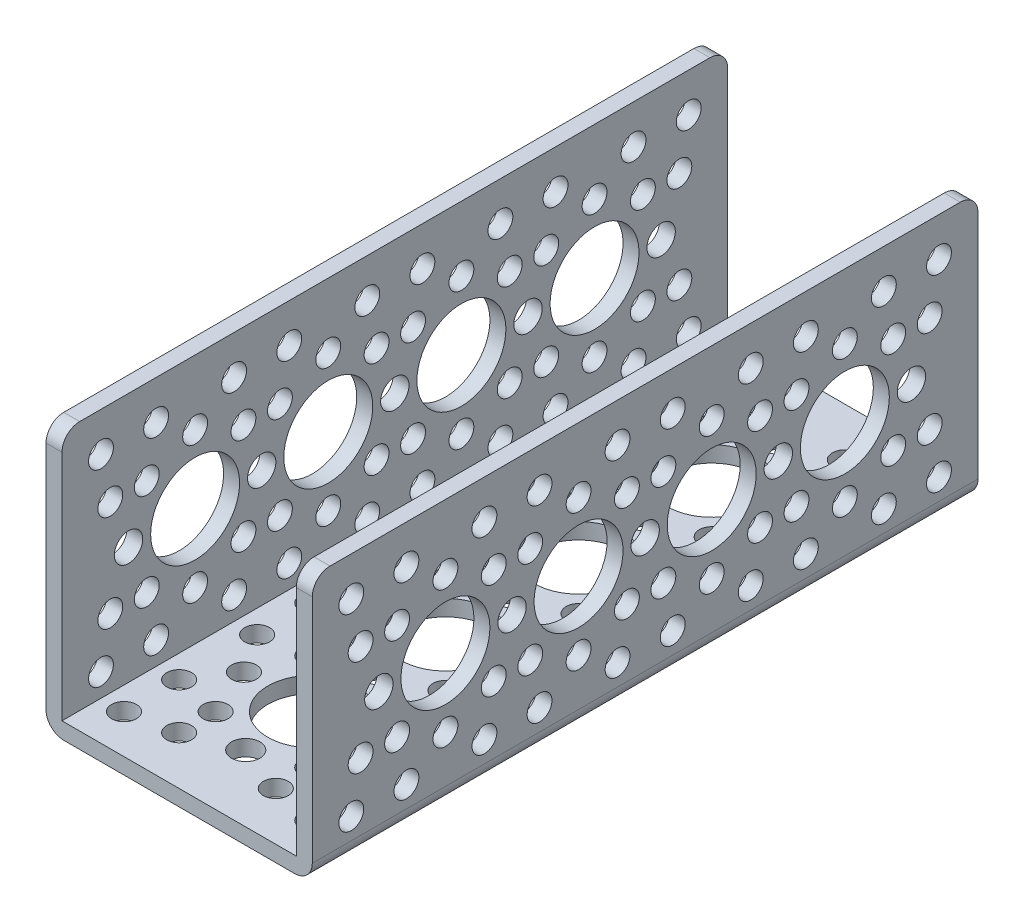
SolidWorks part; units mm, degrees
ref_plane "Front Plane" through (0, 0, 0) normal (0, 0, 1) x (1, 0, 0)
ref_plane "Top Plane" through (0, 0, 0) normal (0, 1, 0) x (1, 0, 0)
ref_plane "Right Plane" through (0, 0, 0) normal (1, 0, 0) x (0, 0, -1)
ref_plane "Plane1" through (0, 0, 0) normal (0, -1, 0) x (1, 0, 0)
sketch "Sketch1" plane through (0, 0, 0) normal (0, -1, 0) x (1, 0, 0)
  line L0 (38.1, 95.25) -> (0, 95.25)
  line L1 (0, 95.25) -> (0, 0)
  line L2 (0, 0) -> (38.1, 0)
  line L3 (38.1, 0) -> (38.1, 95.25)
extrude "Boss-Extrude1" add sketch "Sketch1" against normal blind 38.1
sketch "Sketch2" plane through (0, 0, 95.25) normal (0, 0, 1) x (1, 0, 0)
  line L0 (35.814, 38.1) -> (2.286, 38.1)
  line L1 (2.286, 38.1) -> (2.286, 2.286)
  line L2 (2.286, 2.286) -> (35.814, 2.286)
  line L3 (35.814, 2.286) -> (35.814, 38.1)
extrude "Cut-Extrude1" cut sketch "Sketch2" against normal through all
hole_wizard "Hole1" positions "Sketch4" profile "Sketch3" legacy
sketch "Sketch4" plane through (38.1, 0, 0) normal (1, 0, 0) x (0, 0, -1)
  point P0 (-38.1, 19.05)
  point P1 (-19.05, 19.05)
  point P2 (-57.15, 19.05)
  point P3 (-76.2, 19.05)
sketch "Sketch3" plane through (38.1, 19.05, 38.1) normal (0, 1, 0) x (0, 0, -1)
  line L0 (0, 0) -> (0, 2.286)
  line L1 (0, 2.286) -> (6.3627, 2.286)
  line L2 (6.3627, 2.286) -> (6.3627, 0)
  line L3 (6.3627, 0) -> (0, 0)
  line L4 (0, 110) -> (0, -10) construction
  dimension "Diameter" = 12.7254
  dimension "Depth" = 2.286
hole_wizard "#5 Clearance Hole1" positions "Sketch6" profile "Sketch5" hole size "#5" standard "ANSI Inch"
sketch "Sketch6" plane through (38.1, 0, 0) normal (1, 0, 0) x (0, 0, -1)
  point P0 (-81.7796, 5.5796)
  point P1 (-88.3352, 12.1352)
  point P2 (-81.7796, 32.5204)
  point P3 (-88.3352, 25.9648)
  point P4 (-13.4704, 5.5796)
  point P5 (-6.9148, 12.1352)
  point P6 (-13.4704, 32.5204)
  point P7 (-6.9148, 25.9648)
  point P8 (-62.7296, 5.5796)
  point P9 (-43.6796, 5.5796)
  point P10 (-24.6296, 5.5796)
  point P11 (-62.7296, 32.5204)
  point P12 (-43.6796, 32.5204)
  point P13 (-24.6296, 32.5204)
  point P14 (-89.6704, 5.5796)
  point P15 (-89.6704, 32.5204)
  point P16 (-70.6204, 5.5796)
  point P17 (-70.6204, 32.5204)
  point P18 (-51.5704, 5.5796)
  point P19 (-51.5704, 32.5204)
  point P20 (-38.1, 9.271)
  point P21 (-45.0148, 12.1352)
  point P22 (-45.0148, 25.9648)
  point P23 (-38.1, 28.829)
  point P24 (-31.1852, 25.9648)
  point P25 (-31.1852, 12.1352)
  point P26 (-32.5204, 5.5796)
  point P27 (-32.5204, 32.5204)
  point P28 (-5.5796, 5.5796)
  point P29 (-5.5796, 32.5204)
  point P30 (-12.1352, 12.1352)
  point P31 (-19.05, 9.271)
  point P32 (-25.9648, 12.1352)
  point P33 (-25.9648, 25.9648)
  point P34 (-19.05, 28.829)
  point P35 (-12.1352, 25.9648)
  point P36 (-50.2352, 12.1352)
  point P37 (-69.2852, 12.1352)
  point P38 (-50.2352, 25.9648)
  point P39 (-69.2852, 25.9648)
  point P40 (-57.15, 28.829)
  point P41 (-76.2, 28.829)
  point P42 (-64.0648, 25.9648)
  point P43 (-83.1148, 25.9648)
  point P44 (-64.0648, 12.1352)
  point P45 (-83.1148, 12.1352)
  point P46 (-57.15, 9.271)
  point P47 (-76.2, 9.271)
sketch "Sketch5" plane through (38.1, 5.5796, 81.7796) normal (0, 1, 0) x (0, 0, -1)
  line L0 (0, 0) -> (0, 2.286)
  line L1 (0, 2.286) -> (1.778, 2.286)
  line L2 (1.778, 2.286) -> (1.778, 0)
  line L5 (1.778, 0) -> (0, 0)
  line L11 (0, -6.35) -> (0, 107.95) construction
  dimension "Thru Hole Dia." = 3.556
  dimension "Thru Hole Depth" = 2.286
hole_wizard "#6 Clearance Hole1" positions "Sketch8" profile "Sketch7" hole size "#6" standard "ANSI Inch"
sketch "Sketch8" plane through (38.1, 0, 0) normal (1, 0, 0) x (0, 0, -1)
  point P0 (-85.725, 19.05)
  point P1 (-66.675, 19.05)
  point P2 (-47.625, 19.05)
  point P3 (-28.575, 19.05)
  point P4 (-9.525, 19.05)
sketch "Sketch7" plane through (38.1, 19.05, 85.725) normal (0, 1, 0) x (0, 0, -1)
  line L0 (0, 0) -> (0, 2.286)
  line L1 (0, 2.286) -> (2.032, 2.286)
  line L2 (2.032, 2.286) -> (2.032, 0)
  line L5 (2.032, 0) -> (0, 0)
  line L11 (0, -6.35) -> (0, 107.95) construction
  dimension "Thru Hole Dia." = 4.064
  dimension "Thru Hole Depth" = 2.286
hole_wizard "Hole2" positions "Sketch10" profile "Sketch9" legacy
sketch "Sketch10" plane through (0, 0, 0) normal (0, -1, 0) x (-1, 0, 0)
  point P0 (-19.05, -76.2)
  point P1 (-19.05, -57.15)
  point P2 (-19.05, -38.1)
  point P3 (-19.05, -19.05)
sketch "Sketch9" plane through (19.05, 0, 76.2) normal (1, 0, 0) x (0, 0, -1)
  line L0 (0, 0) -> (0, 38.1)
  line L1 (0, 38.1) -> (6.3627, 38.1)
  line L2 (6.3627, 38.1) -> (6.3627, 0)
  line L3 (6.3627, 0) -> (0, 0)
  line L4 (0, 110) -> (0, -10) construction
  dimension "Diameter" = 12.7254
  dimension "Depth" = 38.1
hole_wizard "#6 Clearance Hole2" positions "Sketch12" profile "Sketch11" hole size "#6" standard "ANSI Inch"
sketch "Sketch12" plane through (0, 0, 0) normal (0, -1, 0) x (-1, 0, 0)
  point P0 (-19.05, -85.725)
  point P1 (-19.05, -66.675)
  point P2 (-19.05, -47.625)
  point P3 (-19.05, -28.575)
  point P4 (-19.05, -9.525)
sketch "Sketch11" plane through (19.05, 0, 85.725) normal (1, 0, 0) x (0, 0, -1)
  line L0 (0, 0) -> (0, 38.1)
  line L1 (0, 38.1) -> (2.032, 38.1)
  line L2 (2.032, 38.1) -> (2.032, 0)
  line L5 (2.032, 0) -> (0, 0)
  line L11 (0, -6.35) -> (0, 107.95) construction
  dimension "Thru Hole Dia." = 4.064
  dimension "Thru Hole Depth" = 38.1
hole_wizard "#5 Clearance Hole2" positions "Sketch14" profile "Sketch13" hole size "#5" standard "ANSI Inch"
sketch "Sketch14" plane through (0, 0, 0) normal (0, -1, 0) x (-1, 0, 0)
  point P0 (-5.5796, -89.6704)
  point P1 (-5.5796, -81.7796)
  point P2 (-12.1352, -88.3352)
  point P3 (-32.5204, -89.6704)
  point P4 (-32.5204, -81.7796)
  point P5 (-25.9648, -88.3352)
  point P6 (-5.5796, -70.6204)
  point P7 (-5.5796, -62.7296)
  point P8 (-32.5204, -70.6204)
  point P9 (-32.5204, -62.7296)
  point P10 (-5.5796, -51.5704)
  point P11 (-5.5796, -43.6796)
  point P12 (-32.5204, -51.5704)
  point P13 (-32.5204, -43.6796)
  point P14 (-12.1352, -69.2852)
  point P15 (-9.271, -76.2)
  point P16 (-12.1352, -83.1148)
  point P17 (-25.9648, -83.1148)
  point P18 (-28.829, -76.2)
  point P19 (-25.9648, -69.2852)
  point P20 (-12.1352, -50.2352)
  point P21 (-9.271, -57.15)
  point P22 (-12.1352, -64.0648)
  point P23 (-25.9648, -64.0648)
  point P24 (-28.829, -57.15)
  point P25 (-25.9648, -50.2352)
  point P26 (-9.271, -38.1)
  point P27 (-12.1352, -45.0148)
  point P28 (-25.9648, -45.0148)
  point P29 (-28.829, -38.1)
  point P30 (-5.5796, -32.5204)
  point P31 (-5.5796, -24.6296)
  point P32 (-12.1352, -31.1852)
  point P33 (-32.5204, -32.5204)
  point P34 (-32.5204, -24.6296)
  point P35 (-25.9648, -31.1852)
  point P36 (-5.5796, -5.5796)
  point P37 (-5.5796, -13.4704)
  point P38 (-12.1352, -6.9148)
  point P39 (-32.5204, -5.5796)
  point P40 (-32.5204, -13.4704)
  point P41 (-25.9648, -6.9148)
  point P42 (-12.1352, -12.1352)
  point P43 (-9.271, -19.05)
  point P44 (-12.1352, -25.9648)
  point P45 (-25.9648, -25.9648)
  point P46 (-28.829, -19.05)
  point P47 (-25.9648, -12.1352)
sketch "Sketch13" plane through (5.5796, 0, 89.6704) normal (1, 0, 0) x (0, 0, -1)
  line L0 (0, 0) -> (0, 38.1)
  line L1 (0, 38.1) -> (1.778, 38.1)
  line L2 (1.778, 38.1) -> (1.778, 0)
  line L5 (1.778, 0) -> (0, 0)
  line L11 (0, -6.35) -> (0, 107.95) construction
  dimension "Thru Hole Dia." = 3.556
  dimension "Thru Hole Depth" = 38.1
hole_wizard "Hole3" positions "Sketch16" profile "Sketch15" legacy
sketch "Sketch16" plane through (0, 0, 0) normal (-1, 0, 0) x (0, 0, 1)
  point P0 (38.1, 19.05)
  point P1 (19.05, 19.05)
  point P2 (57.15, 19.05)
  point P3 (76.2, 19.05)
sketch "Sketch15" plane through (0, 19.05, 38.1) normal (0, 1, 0) x (0, 0, 1)
  line L0 (0, 0) -> (0, 38.1)
  line L1 (0, 38.1) -> (6.3627, 38.1)
  line L2 (6.3627, 38.1) -> (6.3627, 0)
  line L3 (6.3627, 0) -> (0, 0)
  line L4 (0, 110) -> (0, -10) construction
  dimension "Diameter" = 12.7254
  dimension "Depth" = 38.1
hole_wizard "#5 Clearance Hole3" positions "Sketch18" profile "Sketch17" hole size "#5" standard "ANSI Inch"
sketch "Sketch18" plane through (0, 0, 0) normal (-1, 0, 0) x (0, 0, 1)
  point P0 (81.7796, 5.5796)
  point P1 (88.3352, 12.1352)
  point P2 (81.7796, 32.5204)
  point P3 (88.3352, 25.9648)
  point P4 (13.4704, 5.5796)
  point P5 (6.9148, 12.1352)
  point P6 (13.4704, 32.5204)
  point P7 (6.9148, 25.9648)
  point P8 (62.7296, 5.5796)
  point P9 (43.6796, 5.5796)
  point P10 (24.6296, 5.5796)
  point P11 (62.7296, 32.5204)
  point P12 (43.6796, 32.5204)
  point P13 (24.6296, 32.5204)
  point P14 (89.6704, 5.5796)
  point P15 (89.6704, 32.5204)
  point P16 (70.6204, 5.5796)
  point P17 (70.6204, 32.5204)
  point P18 (51.5704, 5.5796)
  point P19 (51.5704, 32.5204)
  point P20 (31.1852, 12.1352)
  point P21 (38.1, 9.271)
  point P22 (45.0148, 12.1352)
  point P23 (45.0148, 25.9648)
  point P24 (38.1, 28.829)
  point P25 (31.1852, 25.9648)
  point P26 (32.5204, 5.5796)
  point P27 (32.5204, 32.5204)
  point P28 (5.5796, 5.5796)
  point P29 (5.5796, 32.5204)
  point P30 (12.1352, 12.1352)
  point P31 (19.05, 9.271)
  point P32 (25.9648, 12.1352)
  point P33 (25.9648, 25.9648)
  point P34 (19.05, 28.829)
  point P35 (12.1352, 25.9648)
  point P36 (50.2352, 25.9648)
  point P37 (69.2852, 25.9648)
  point P38 (57.15, 28.829)
  point P39 (76.2, 28.829)
  point P40 (64.0648, 25.9648)
  point P41 (83.1148, 25.9648)
  point P42 (64.0648, 12.1352)
  point P43 (83.1148, 12.1352)
  point P44 (57.15, 9.271)
  point P45 (76.2, 9.271)
  point P46 (50.2352, 12.1352)
  point P47 (69.2852, 12.1352)
sketch "Sketch17" plane through (0, 5.5796, 81.7796) normal (0, 1, 0) x (0, 0, 1)
  line L0 (0, 0) -> (0, 38.1)
  line L1 (0, 38.1) -> (1.778, 38.1)
  line L2 (1.778, 38.1) -> (1.778, 0)
  line L5 (1.778, 0) -> (0, 0)
  line L11 (0, -6.35) -> (0, 107.95) construction
  dimension "Thru Hole Dia." = 3.556
  dimension "Thru Hole Depth" = 38.1
hole_wizard "#6 Clearance Hole3" positions "Sketch20" profile "Sketch19" hole size "#6" standard "ANSI Inch"
sketch "Sketch20" plane through (0, 0, 0) normal (-1, 0, 0) x (0, 0, 1)
  point P0 (85.725, 19.05)
  point P1 (66.675, 19.05)
  point P2 (47.625, 19.05)
  point P3 (28.575, 19.05)
  point P4 (9.525, 19.05)
sketch "Sketch19" plane through (0, 19.05, 85.725) normal (0, 1, 0) x (0, 0, 1)
  line L0 (0, 0) -> (0, 38.1)
  line L1 (0, 38.1) -> (2.032, 38.1)
  line L2 (2.032, 38.1) -> (2.032, 0)
  line L5 (2.032, 0) -> (0, 0)
  line L11 (0, -6.35) -> (0, 107.95) construction
  dimension "Thru Hole Dia." = 4.064
  dimension "Thru Hole Depth" = 38.1
fillet "Fillet1" radius 2.54 6 edges at (1.143, 38.1, 95.25) (36.957, 38.1, 95.25) (36.957, 38.1, 0) (38.1, 0, 47.625) (1.143, 38.1, 0) (0, 0, 47.625)
